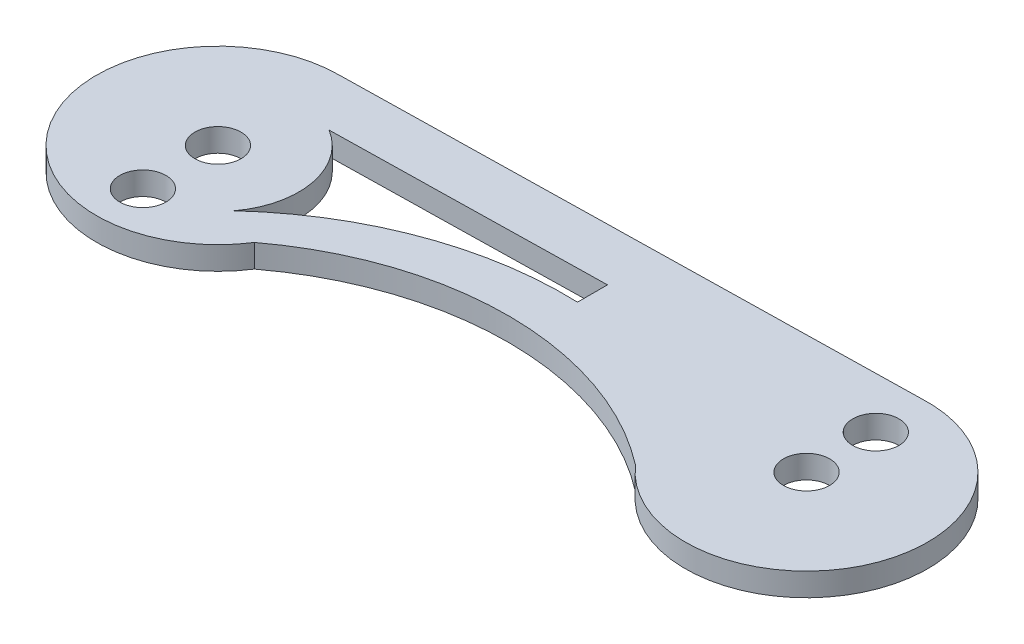
SolidWorks part; units mm, degrees
ref_plane "Front Plane" through (0, 0, 0) normal (0, 0, 1) x (1, 0, 0)
ref_plane "Top Plane" through (0, 0, 0) normal (0, 1, 0) x (1, 0, 0)
ref_plane "Right Plane" through (0, 0, 0) normal (1, 0, 0) x (0, 0, -1)
sketch "Sketch1" plane through (0, 0, 0) normal (0, 1, 0) x (1, 0, 0)
  line L0 (-33.6615, 9.5583) -> (15.7468, 10.4937)
  line L1 (-29.9961, 4.991) -> (-6.3374, 5.4389)
  line L2 (-6.3374, 5.4389) -> (-6.3374, 2.8411)
  circle A0 centre (-33.6615, -0.9726) radius 2
  arc A1 (8.397, -6.8704) -> (15.7468, 10.4937) centre (16.3288, 0.0098) ccw
  arc A2 (-28.0675, -5.1805) -> (-29.9961, 4.991) centre (-33.6615, -0.9726) ccw
  arc A4 (-24.8046, -6.6696) -> (8.397, -6.8704) centre (-8.3354, -28.5449) cw
  arc A5 (-28.0675, -5.1805) -> (-6.3374, 2.8411) centre (-7.4528, -27.5807) cw
  arc A6 (-33.6615, 9.5583) -> (-24.8046, -6.6696) centre (-33.6615, -0.9726) ccw
  circle A7 centre (-33.6615, -7.4726) radius 2
  circle A8 centre (16.3288, 0.0098) radius 2
  circle A9 centre (16.3288, 6.0098) radius 2
  point P8 (-29.9961, 4.991)
  point P11 (-24.8046, -6.6696)
  point P12 (-28.0675, -5.1805)
  dimension "D1" = 4
  dimension "D2" = 21
  dimension "D3" = 14
  dimension "D6" = 4
  dimension "D7" = 4
  dimension "D8" = 4
  dimension "D5" = 50
  dimension "D10" = 6
  dimension "D11" = 6.5
extrude "Boss-Extrude5" add sketch "Sketch1" along normal blind 2
